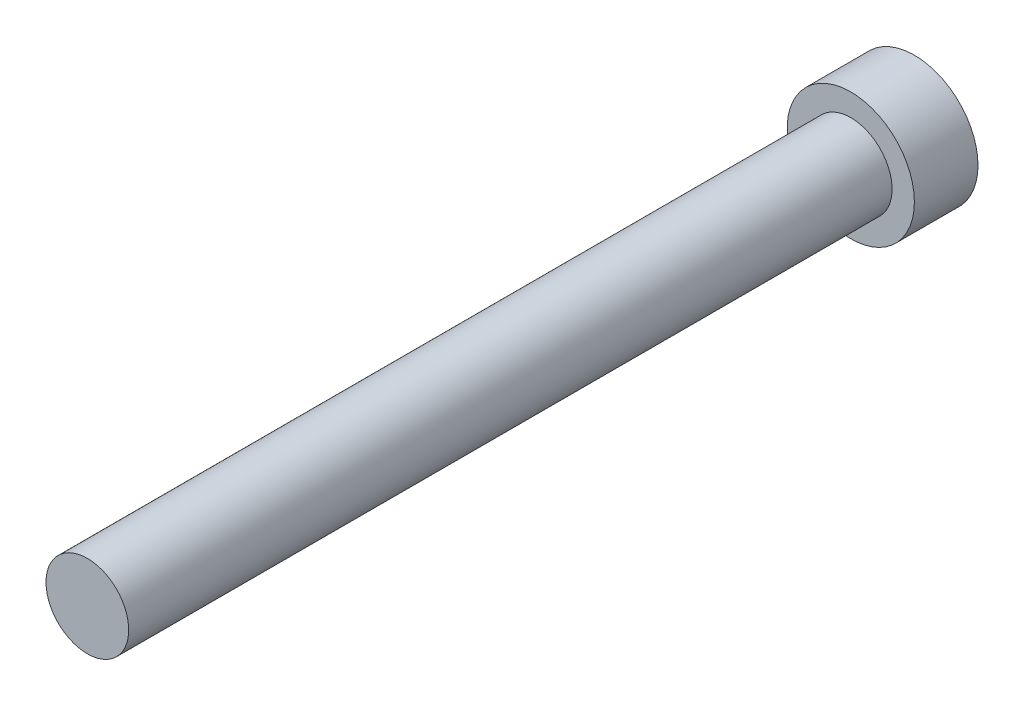
SolidWorks part; units mm, degrees
ref_plane "Front Plane" through (0, 0, 0) normal (0, 0, 1) x (1, 0, 0)
ref_plane "Top Plane" through (0, 0, 0) normal (0, 1, 0) x (1, 0, 0)
ref_plane "Right Plane" through (0, 0, 0) normal (1, 0, 0) x (0, 0, -1)
sketch "Sketch1" plane through (0, 0, 0) normal (0, 0, 1) x (1, 0, 0)
  circle A0 centre (0, 0) radius 2.54
extrude "Boss-Extrude1" add sketch "Sketch1" along normal blind 2.54
sketch "Sketch2" plane through (0, 0, 2.54) normal (0, 0, 1) x (1, 0, 0)
  circle A0 centre (0, 0) radius 1.651
extrude "Boss-Extrude2" add sketch "Sketch2" along normal blind 30.48
